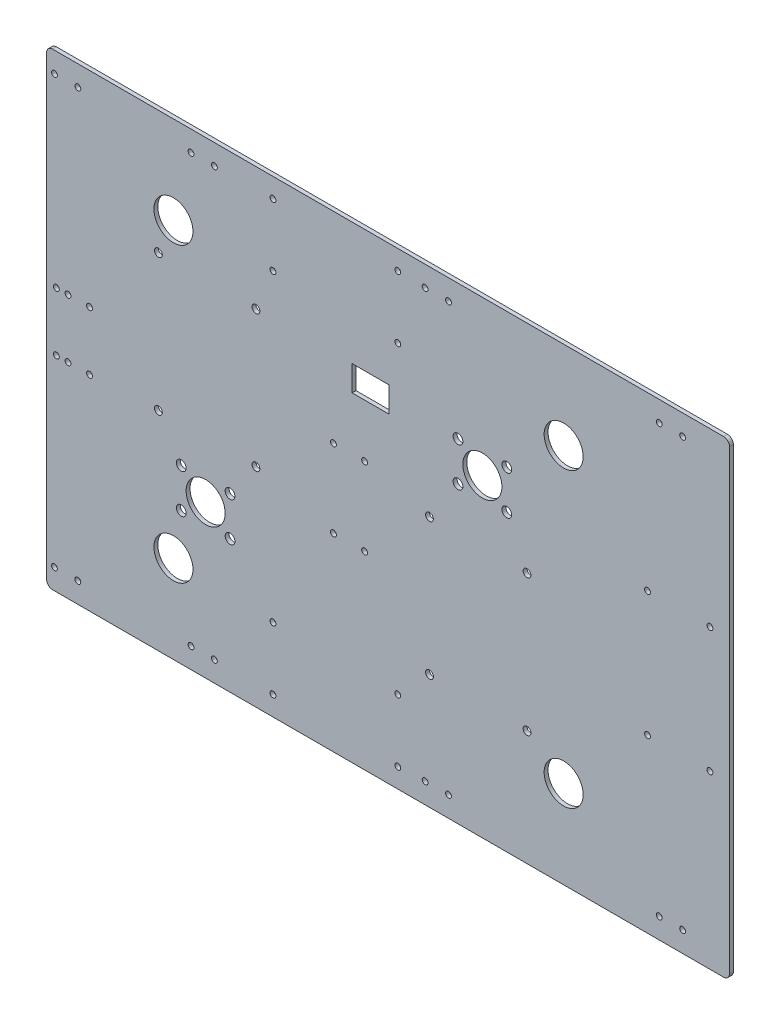
SolidWorks part; units mm, degrees
ref_plane "前视基准面" through (0, 0, 0) normal (0, 0, 1) x (1, 0, 0)
ref_plane "上视基准面" through (0, 0, 0) normal (0, 1, 0) x (1, 0, 0)
ref_plane "右视基准面" through (0, 0, 0) normal (1, 0, 0) x (0, 0, -1)
sketch "Model" plane through (0, 0, 0) normal (0, 0, 1) x (1, 0, 0)
  line L0 (347, 120) -> (3, 120)
  line L1 (350, -117) -> (350, 117)
  line L2 (3, -120) -> (347, -120)
  line L3 (0, 117) -> (0, -117)
  line L4 (156.5896, 57.1757) -> (175.5896, 57.1757)
  line L5 (175.5896, 57.1757) -> (175.5896, 44.1757)
  line L6 (175.5896, 44.1757) -> (156.5896, 44.1757)
  line L7 (156.5896, 44.1757) -> (156.5896, 57.1757)
  line L8 (0, 0) -> (350, 0) construction
  arc A0 (350, 117) -> (347, 120) centre (347, 117) ccw
  arc A1 (347, -120) -> (350, -117) centre (347, -117) ccw
  arc A2 (0, -117) -> (3, -120) centre (3, -117) ccw
  arc A3 (3, 120) -> (0, 117) centre (3, 117) ccw
  circle A4 centre (4, 109.5) radius 1.5
  circle A5 centre (16, 109.5) radius 1.5
  circle A6 centre (74, 109.5) radius 1.5
  circle A7 centre (86, 109.5) radius 1.5
  circle A8 centre (194, 109.5) radius 1.5
  circle A9 centre (206, 109.5) radius 1.5
  circle A10 centre (314, 109.5) radius 1.5
  circle A11 centre (326, 109.5) radius 1.5
  circle A12 centre (5, 15) radius 1.5
  circle A13 centre (22, 15) radius 1.5
  circle A14 centre (147, 17) radius 1.5
  circle A15 centre (163, 17) radius 1.5
  circle A16 centre (308, 32) radius 1.5
  circle A17 centre (340, 32) radius 1.5
  circle A18 centre (147, -23) radius 1.5
  circle A19 centre (163, -23) radius 1.5
  circle A20 centre (340, -32) radius 1.5
  circle A21 centre (308, -32) radius 1.5
  circle A22 centre (5, -15) radius 1.5
  circle A23 centre (22, -15) radius 1.5
  circle A24 centre (326, -109.5) radius 1.5
  circle A25 centre (314, -109.5) radius 1.5
  circle A26 centre (206, -109.5) radius 1.5
  circle A27 centre (194, -109.5) radius 1.5
  circle A28 centre (4, -109.5) radius 1.5
  circle A29 centre (16, -109.5) radius 1.5
  circle A30 centre (86, -109.5) radius 1.5
  circle A31 centre (74, -109.5) radius 1.5
  circle A32 centre (116, 110) radius 1.5
  circle A33 centre (180, 110) radius 1.5
  circle A34 centre (180, 78) radius 1.5
  circle A35 centre (116, 78) radius 1.5
  circle A36 centre (116, -110) radius 1.5
  circle A37 centre (116, -78) radius 1.5
  circle A38 centre (180, -110) radius 1.5
  circle A39 centre (180, -78) radius 1.5
  circle A40 centre (65, 75) radius 10
  circle A41 centre (265, 75) radius 10
  circle A42 centre (65, -75) radius 10
  circle A43 centre (265, -75) radius 10
  circle A44 centre (196.2331, 8.9876) radius 2
  circle A45 centre (246.2331, 8.9876) radius 2
  circle A46 centre (246.2331, -61.0124) radius 2
  circle A47 centre (196.2331, -61.0124) radius 2
  circle A48 centre (57.2911, 56.7427) radius 2
  circle A49 centre (107.2911, 56.7427) radius 2
  circle A50 centre (107.2911, -13.2573) radius 2
  circle A51 centre (57.2911, -13.2573) radius 2
  circle A52 centre (223.3563, 40.8665) radius 10
  circle A53 centre (235.8563, 50.8665) radius 2.5
  circle A54 centre (235.8563, 30.8665) radius 2.5
  circle A55 centre (210.8563, 50.8665) radius 2.5
  circle A56 centre (210.8563, 30.8665) radius 2.5
  circle A57 centre (81.504, -41.835) radius 10
  circle A58 centre (94.004, -31.835) radius 2.5
  circle A59 centre (94.004, -51.835) radius 2.5
  circle A60 centre (69.004, -31.835) radius 2.5
  circle A61 centre (69.004, -51.835) radius 2.5
  circle A62 centre (11, 15) radius 1.5
  circle A63 centre (11, -15) radius 1.5
  point P132 (262.5253, 120)
  point P133 (255.51, -120)
  dimension "D2" = 30
  dimension "D3" = 3
  dimension "D4" = 11
  dimension "D1" = 240
extrude "凸台-拉伸1" add sketch "Model" along normal blind 2
